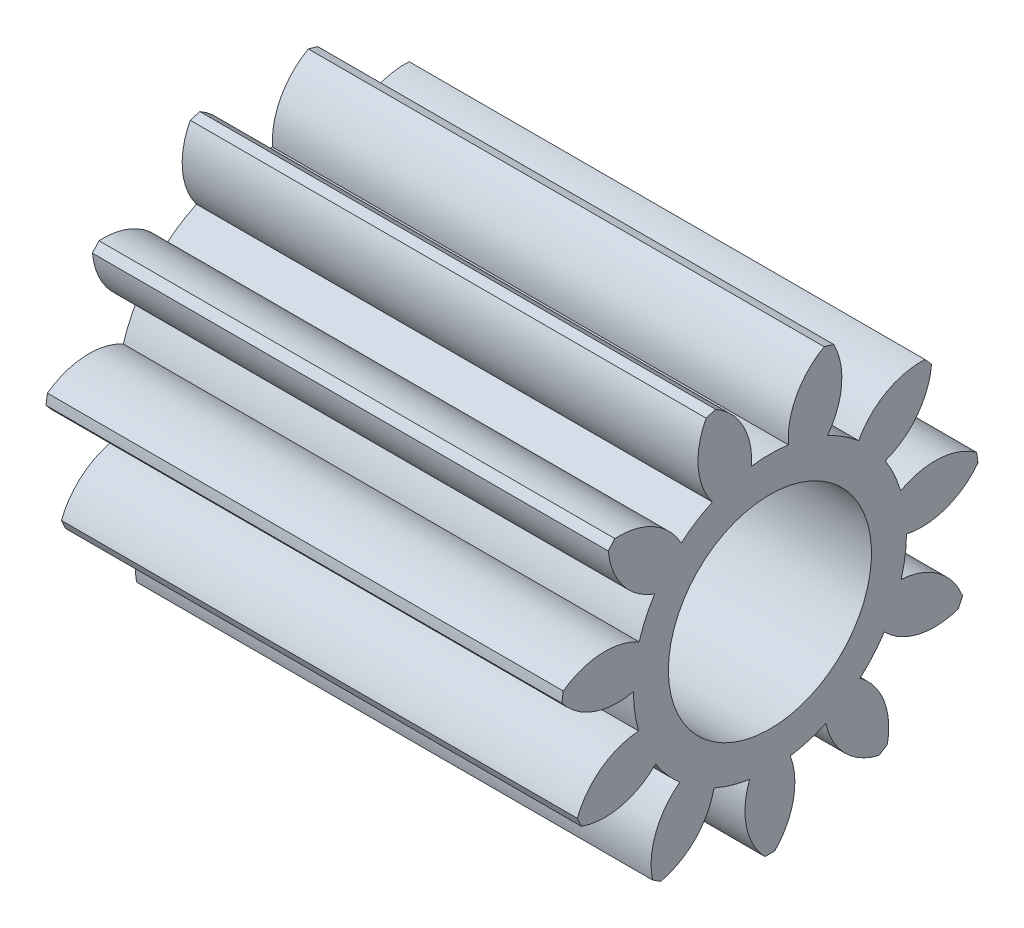
SolidWorks part; units mm, degrees
ref_plane "Plane1" through (0, 0, 0) normal (0, 0, 1) x (1, 0, 0)
ref_plane "Plane2" through (0, 0, 0) normal (0, 1, 0) x (1, 0, 0)
ref_plane "Plane3" through (0, 0, 0) normal (1, 0, 0) x (0, 0, -1)
other "Configuration Table"
sketch "HoldingSke" plane through (0, 0, 0) normal (0, 1, 0) x (1, 0, 0)
  line L0 (0, 0) -> (797.8666, -155.0896)
  line L1 (-15, 0) -> (100, 0) construction
  line L2 (0, 0) -> (-2.1039, 2.3779)
  line L3 (0, 0) -> (-11.863, 4.5341)
  line L4 (0, 0) -> (8.4773, 1.6478)
  line L5 (0, 0) -> (-47.5972, -17.7524)
  line L6 (0, 0) -> (-10.5278, -7.1032)
  line L7 (-2.1039, 2.3779) -> (8.8308, 51.9871)
  line L8 (-76.2, 54.61) -> (-75.184, 54.61)
  line L9 (-71.009, 38.7566) -> (-53.1078, 45.2721)
  line L10 (-76.2, 71.12) -> (104.1128, 71.12)
  line L11 (0, 0) -> (-12.7, 0)
  line L12 (-76.2, 101.6) -> (-76.1716, 101.6)
  line L13 (24.9733, 27.94) -> (52.9518, 28.4284)
  line L14 (24.9733, 27.94) -> (25.0241, 27.9398)
  line L15 (24.9733, 27.94) -> (100.4021, 29.52)
  circle A0 centre (0, 0) radius 0.3969
  circle A1 centre (0, 0) radius 3.3623
  circle A2 centre (0, 0) radius 38.1
  circle A3 centre (0, 0) radius 0.3969
  dimension "MHD" = 6.7246
  dimension "Hub_dia" = 76.2
  dimension "Bore" = 0.7937
  dimension "MBD" = 0.7937
  dimension "Num_teeth" = 11
  dimension "Pitch" = 812.8
  dimension "Overall_len" = 50.8
  dimension "Show_teeth" = 11
  dimension "Thickness" = 12.7
  dimension "OAL" = 50.8001
  dimension "T_dim" = 1.016
  dimension "Ap" = 20
  dimension "H" = 19.05
  dimension "Pitch_radius" = 180.3128
  dimension "Width" = 12.7
  dimension "Backlash" = 0.0284
  dimension "Addendum_fac" = 1
  dimension "Dedendum_fac" = 1.2
  dimension "Clearance_fac" = 0.2
  dimension "Dedendum_add" = 0.0508
sketch "BasProSke" plane through (0, 0, 0) normal (0, 1, 0) x (1, 0, 0)
  line L0 (-10, 0) -> (60, 0) construction
  line L1 (0, 0) -> (0, 5.1594)
  line L2 (0, 0) -> (12.7, 0)
  line L3 (12.7, 0) -> (12.7, 5.1594)
  line L4 (12.7, 5.1594) -> (0, 5.1594)
  dimension "Thickness" = 12.7
  dimension "Diameter" = 10.3187
revolve "Base-Revolve" add sketch "BasProSke" angle 360 about L0
sketch "TooCutSke" plane through (0, 0, 0) normal (1, 0, 0) x (0, 0, -1)
  line L1 (0, 0) -> (0, 107) construction
  line L2 (0, 0) -> (-0.671, 4.3138) construction
  line L3 (0, 0) -> (-2.4387, 8.3055) construction
  line L4 (-0.671, 4.3138) -> (-1.2194, 4.1527) construction
  arc A0 (0.4557, 3.3313) -> (-0.4557, 3.3313) centre (0, 0) ccw
  arc A1 (1.3674, 5.0012) -> (-1.3674, 5.0012) centre (0, 0) ccw
  circle A2 centre (0, 0) radius 4.3656 construction
  circle A3 centre (0, 0) radius 4.1023 construction
  arc A4 (-0.4557, 3.3313) -> (-1.3674, 5.0012) centre (-2.1969, 3.4645) ccw
  arc A5 (1.3674, 5.0012) -> (0.4557, 3.3313) centre (2.1969, 3.4645) ccw
  dimension "Root_dia" = 6.7246
  dimension "Overcut_dia" = 10.3696
  dimension "Pitch_dia" = 8.7312
  dimension "Base_dia" = 8.2047
  dimension "Flank_rad" = 1.7463
  dimension "Half_ang" = 16.364
  dimension "Half_CT" = 0.5715
extrude "ToothCut" cut sketch "TooCutSke" along normal through all
fillet "Breaks" [suppressed] radius 0.0159
fillet "RootFillets" [suppressed] radius 0.2095
pattern_circular "TeethCuts" count 11 every 32.727 about axis through (-10, 0, 0) along (1, 0, 0) of "ToothCut", "RootFillets", "Breaks"
sketch "HubNeaOneSke" plane through (0, 0, 0) normal (-1, 0, 0) x (0, 0, 1)
  circle A0 centre (0, 0) radius 3.3623
  dimension "Diameter" = 6.7246
extrude "HubNearOne" [suppressed] add sketch "HubNeaOneSke" along normal blind 38.1001
sketch "HubNeaBotSke" plane through (0, 0, 0) normal (-1, 0, 0) x (0, 0, 1)
  circle A0 centre (0, 0) radius 3.3623
  dimension "Diameter" = 6.7246
extrude "HubNearBoth" [suppressed] add sketch "HubNeaBotSke" along normal blind 19.05
ref_plane "FarPln" through (12.7, 0, 0) normal (1, 0, 0) x (0, 0, -1)
sketch "HubFarSke" plane through (12.7, 0, 0) normal (1, 0, 0) x (0, 0, -1)
  circle A0 centre (0, 0) radius 3.3623
  dimension "Diameter" = 6.7246
extrude "HubFar" [suppressed] add sketch "HubFarSke" along normal blind 19.05
sketch "BorSke" plane through (0, 0, 0) normal (1, 0, 0) x (0, 0, -1)
  circle A0 centre (0, 0) radius 2.5
  dimension "Diameter" = 5
extrude "Bore" cut sketch "BorSke" along normal mid plane 101.6001
sketch "KeySke" plane through (0, 0, 0) normal (1, 0, 0) x (0, 0, -1)
  line L0 (-0.127, 0) -> (-0.127, 0.6191)
  line L1 (-0.127, 0.6191) -> (0.127, 0.6191)
  line L2 (0.127, 0.6191) -> (0.127, 0)
  line L3 (0, 0) -> (0, 34) construction
  line L4 (-0.127, 0) -> (0.127, 0)
  dimension "Offset" = 0.6191
  dimension "Width" = 0.254
extrude "Keyway" [suppressed] cut sketch "KeySke" along normal mid plane 101.6001
pattern_circular "Keyway2" [suppressed] count 2 every 90 about axis through (-10, 0, 0) along (1, 0, 0)
equation "' \"Pitch@HoldingSke\" = 4"
equation "' \"Num_teeth@HoldingSke\" = 12"
equation "' \"Ap@HoldingSke\" =  20"
equation "' \"Ap@HoldingSke\" = 20"
equation "' \"Width@HoldingSke\" = 0.5"
equation "' \"Hub_dia@HoldingSke\"= 1"
equation "' \"Hub_dia@HoldingSke\" = 1"
equation "' \"Overall_len@HoldingSke\" = 1.0"
equation "' \"Bore@HoldingSke\" = 0.75"
equation "' \"T_dim@HoldingSke\" = 0.85"
equation "' \"Width@KeySke\" = 0.25"
equation "' \"Show_teeth@HoldingSke\" = 13"
equation "' \"Backlash@HoldingSke\" = 0.009"
equation "' \"Addendum_fac@HoldingSke\" = 1.0"
equation "' \"Dedendum_fac@HoldingSke\" = 1.25"
equation "' \"Dedendum_add@HoldingSke\" = 0.00005"
equation "' \"Clearance_fac@HoldingSke\" = 0.25"
equation "' \"Pitch@HoldingSke\" = 0.5"
equation "' \"Num_teeth@HoldingSke\" = 23"
equation "' \"Show_teeth@HoldingSke\" = 23"
equation "' \"Backlash@HoldingSke\" = 0.0375"
equation "\"Overcut_dia@TooCutSke\" = (\"Num_teeth@HoldingSke\" + 2 * \"Addendum_fac@HoldingSke\") / \"Pitch@HoldingSke\" + 0.002"
equation "\"Pitch_dia@TooCutSke\" = \"Num_teeth@HoldingSke\" / \"Pitch@HoldingSke\""
equation "\"Base_dia@TooCutSke\" = \"Num_teeth@HoldingSke\" / \"Pitch@HoldingSke\" * cos((\"Ap@HoldingSke\"  * 3.14159265 / 180))"
equation "\"Root_dia@TooCutSke\" = (\"Num_teeth@HoldingSke\" + 2) / \"Pitch@HoldingSke\" - 2 * (\"Addendum_fac@HoldingSke\" + \"Dedendum_fac@HoldingSke\") / \"Pitch@HoldingSke\" - \"Dedendum_add@HoldingSke\" * 2"
equation "\"Half_ang@TooCutSke\" = 180 / \"Num_teeth@HoldingSke\""
equation "\"Half_CT@TooCutSke\" = \"Num_teeth@HoldingSke\" / \"Pitch@HoldingSke\" * sin((3.14159265 / 2 / \"Num_teeth@HoldingSke\")) / 2 - 7 * \"Backlash@HoldingSke\" / 4"
equation "\"Flank_rad@TooCutSke\" = \"Num_teeth@HoldingSke\" / \"Pitch@HoldingSke\" / 5"
equation "\"Radius@RootFillets\" = \"Clearance_fac@HoldingSke\" / \"Pitch@HoldingSke\" + \"Dedendum_add@HoldingSke\""
equation "\"Break_rad@Breaks\" = 0.02 / \"Pitch@HoldingSke\""
equation "\"Thickness@HoldingSke\" = \"Width@HoldingSke\""
equation "\"OAL@HoldingSke\" = \"Thickness@HoldingSke\""
equation "\"MHD@HoldingSke\" = (\"Num_teeth@HoldingSke\" + 2) / \"Pitch@HoldingSke\" - 2 * (\"Addendum_fac@HoldingSke\" + \"Dedendum_fac@HoldingSke\")  / \"Pitch@HoldingSke\" - \"Dedendum_add@HoldingSke\" * 2"
equation "\"MBD@HoldingSke\" = (\"Num_teeth@HoldingSke\" + 2) / \"Pitch@HoldingSke\" - 2 * (\"Addendum_fac@HoldingSke\" + \"Dedendum_fac@HoldingSke\")  / \"Pitch@HoldingSke\" - \"Dedendum_add@HoldingSke\" * 2 - 0.002"
equation "\"MHD@HoldingSke\" = ((sgn( \"MHD@HoldingSke\" - \"Hub_dia@HoldingSke\" )-1)*( \"MHD@HoldingSke\" - \"Hub_dia@HoldingSke\" ))/-2+ \"Hub_dia@HoldingSke\""
equation "\"MBD@HoldingSke\" = ((sgn( \"MBD@HoldingSke\" - \"Bore@HoldingSke\" )-1)*( \"MBD@HoldingSke\" - \"Bore@HoldingSke\" ))/-2+ \"Bore@HoldingSke\""
equation "\"OAL@HoldingSke\" = ((sgn( \"OAL@HoldingSke\" - \"Overall_len@HoldingSke\" )+1)*( \"OAL@HoldingSke\" - \"Overall_len@HoldingSke\" ))/2 + \"Overall_len@HoldingSke\" + 0.000002"
equation "\"Num_teeth@TeethCuts\" = int( \"Show_teeth@HoldingSke\" ) + 1"
equation "\"Num_teeth@TeethCuts\" = ((sgn( \"Num_teeth@TeethCuts\" - \"Num_teeth@HoldingSke\" )-1)*( \"Num_teeth@TeethCuts\" - \"Num_teeth@HoldingSke\" ))/-2+ \"Num_teeth@HoldingSke\""
equation "\"Num_teeth@TeethCuts\" = ((sgn( \"Num_teeth@TeethCuts\" - 2.0)+1)*( \"Num_teeth@TeethCuts\" - 2.0))/2 +2.0"
equation "\"Angle@TeethCuts\" = 360.0 / \"Num_teeth@HoldingSke\""
equation "\"Diameter@BasProSke\" = (\"Num_teeth@HoldingSke\" + 2 * \"Addendum_fac@HoldingSke\") / \"Pitch@HoldingSke\""
equation "\"Thickness@BasProSke\"  = \"Thickness@HoldingSke\""
equation "' \"Fillet_rad@BasProSke\" =  \"Thickness@HoldingSke\" * 0.05"
equation "' \"Fillet_rad@BasProSke\" = \"Thickness@HoldingSke\" * 0.05"
equation "\"MHD@HoldingSke\" = ((sgn( \"MHD@HoldingSke\" - \"Root_dia@TooCutSke\" )-1)*( \"MHD@HoldingSke\" - \"Root_dia@TooCutSke\" ))/-2+ \"Root_dia@TooCutSke\""
equation "\"Diameter@HubNeaOneSke\" = \"MHD@HoldingSke\""
equation "\"Length@HubNearOne\" = \"OAL@HoldingSke\" - \"Thickness@BasProSke\""
equation "\"Diameter@HubNeaBotSke\" = \"MHD@HoldingSke\""
equation "\"Length@HubNearBoth\" = ( \"OAL@HoldingSke\" - \"Thickness@BasProSke\" ) / 2.0"
equation "\"Thickness@FarPln\" = \"Thickness@BasProSke\""
equation "\"Diameter@HubFarSke\" = \"MHD@HoldingSke\""
equation "\"Length@HubFar\" = ( \"OAL@HoldingSke\" - \"Thickness@BasProSke\" ) / 2.0"
equation "\"Diameter@BorSke\"=5mm"
equation "\"D1@Bore\" = \"OAL@HoldingSke\" * 2.0"
equation "\"D1@Keyway\" = \"OAL@HoldingSke\" * 2.0"
equation "\"Offset@KeySke\" = \"T_dim@HoldingSke\" - \"MBD@HoldingSke\" / 2.0"
